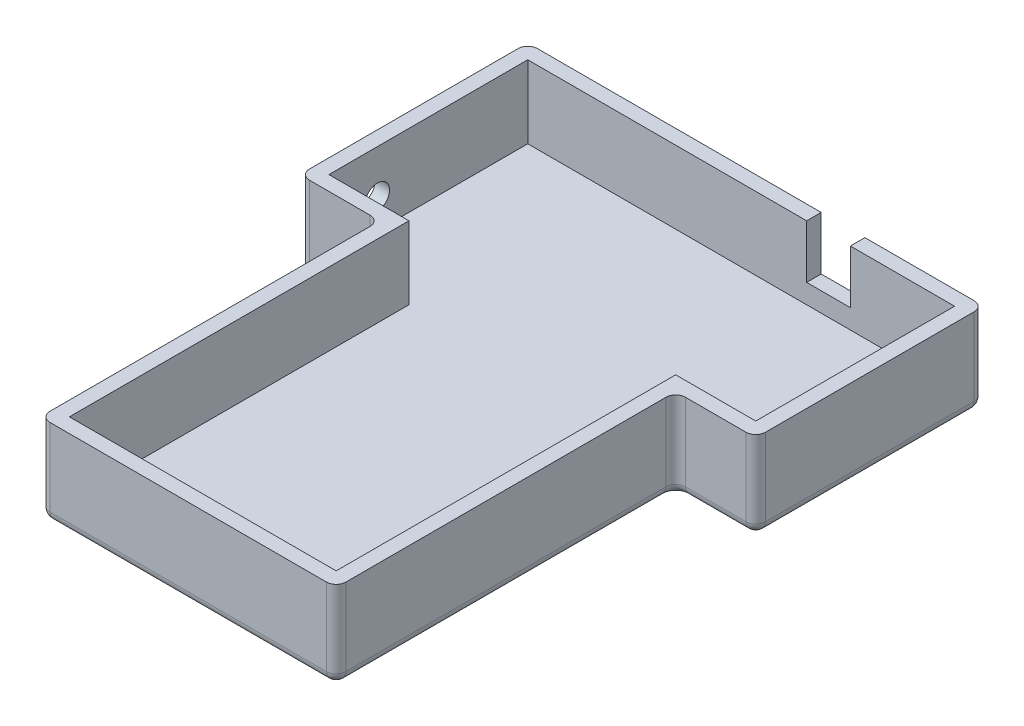
SolidWorks part; units mm, degrees
material "PEI"
ref_plane "Front Plane" through (0, 0, 0) normal (0, 0, 1) x (1, 0, 0)
ref_plane "Top Plane" through (0, 0, 0) normal (0, 1, 0) x (1, 0, 0)
ref_plane "Right Plane" through (0, 0, 0) normal (1, 0, 0) x (0, 0, -1)
sketch "Sketch1" plane through (0, 0, 0) normal (0, 1, 0) x (1, 0, 0)
  line L0 (0, 0) -> (88, 0)
  line L1 (88, 0) -> (88, -41)
  line L2 (88, -41) -> (71.5, -41)
  line L3 (71.5, -41) -> (71.5, -111)
  line L4 (71.5, -111) -> (16.5, -111)
  line L5 (16.5, -111) -> (16.5, -41)
  line L6 (16.5, -41) -> (0, -41)
  line L7 (0, -41) -> (0, 0)
  dimension "D1" = 88
  dimension "D2" = 55
  dimension "D3" = 41
  dimension "D4" = 70
extrude "Boss-Extrude1" add sketch "Sketch1" along normal blind 15
shell "Shell1" thickness 3
sketch "Sketch3" plane through (0, 0, -3) normal (0, 0, -1) x (-1, 0, 0)
  line L0 (-91, 6) -> (3, 6) construction
  line L1 (-91, 15) -> (-91, -3) construction
  line L2 (3, 15) -> (3, -3) construction
  line L3 (-44, 6) -> (-44, -3) construction
  line L4 (-91, -3) -> (3, -3) construction
  line L5 (-44, -3) -> (-44, 15) construction
  line L6 (-91, 15) -> (3, 15) construction
  line L8 (-66.5, 15) -> (-57.5, 15)
  line L9 (-66.5, 15) -> (-66.5, 4)
  line L10 (-66.5, 4) -> (-57.5, 4)
  line L11 (-57.5, 15) -> (-57.5, 4)
  line L12 (-66.5, 15) -> (-57.5, 4) construction
  line L13 (-66.5, 4) -> (-57.5, 15) construction
  point P13 (-62, 9.5)
  point P18 (-44, 1.5)
  dimension "D1" = 11
  dimension "D2" = 9
  dimension "D3" = 13.5
  dimension "D4" = 0
extrude "Cut-Extrude1" cut sketch "Sketch3" against normal blind 3
sketch "Sketch4" plane through (-3, 0, 0) normal (-1, 0, 0) x (0, 0, 1)
  line L0 (44, 15) -> (44, -3) construction
  line L1 (-3, 15) -> (44, 15) construction
  circle A0 centre (31, 6) radius 2.5
  dimension "D1" = 5
  dimension "D2" = 13
  dimension "D3" = 9
extrude "Cut-Extrude2" cut sketch "Sketch4" against normal blind 3
fillet "Fillet1" radius 2 16 edges at (5.25, -3, 44) (13.5, -3, 79) (44, -3, 114) (74.5, -3, 79) (82.75, -3, 44) (91, -3, 20.5) (44, -3, -3) (-3, -3, 20.5) (-3, 6, -3) (91, 6, -3) (91, 6, 44) (74.5, 6, 44) (74.5, 6, 114) (13.5, 6, 114) (13.5, 6, 44) (-3, 6, 44)
